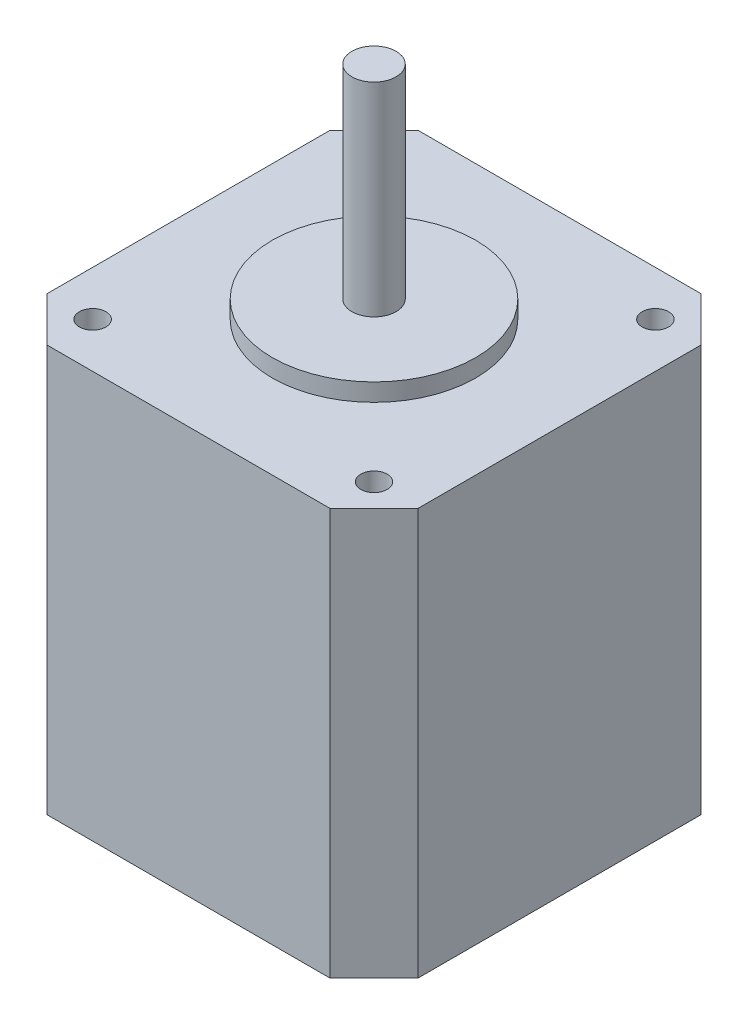
SolidWorks part; units mm, degrees
ref_plane "Front Plane" through (0, 0, 0) normal (0, 0, 1) x (1, 0, 0)
ref_plane "Top Plane" through (0, 0, 0) normal (0, 1, 0) x (1, 0, 0)
ref_plane "Right Plane" through (0, 0, 0) normal (1, 0, 0) x (0, 0, -1)
sketch "Sketch1" plane through (0, 0, 0) normal (0, 1, 0) x (1, 0, 0)
  line L1 (-21, -21) -> (21, -21)
  line L2 (-21, -21) -> (-21, 21)
  line L3 (-21, 21) -> (21, 21)
  line L4 (21, -21) -> (21, 21)
  line L5 (-21, -21) -> (21, 21) construction
  line L6 (-21, 21) -> (21, -21) construction
  point P0 (0, 0)
  dimension "D1" = 42
  dimension "D2" = 42
extrude "Boss-Extrude1" add sketch "Sketch1" along normal blind 46
chamfer "Chamfer1" distance 5 angle 45 4 edges at (-21, 23, -21) (21, 23, -21) (21, 23, 21) (-21, 23, 21)
sketch "Sketch2" plane through (0, 46, 0) normal (0, 1, 0) x (1, 0, 0)
  circle A0 centre (0, 0) radius 11.5
  dimension "D1" = 23
extrude "Boss-Extrude2" add sketch "Sketch2" along normal blind 2
sketch "Sketch3" plane through (0, 46, 0) normal (0, 1, 0) x (1, 0, 0)
  circle A0 centre (0, 0) radius 2.5
  dimension "D1" = 5
extrude "Boss-Extrude3" add sketch "Sketch3" along normal blind 25
sketch "Sketch4" plane through (0, 46, 0) normal (0, 1, 0) x (1, 0, 0)
  line L0 (-15.9099, -15.9099) -> (-15.9099, 15.9099) construction
  line L1 (-15.9099, 15.9099) -> (15.9099, 15.9099) construction
  circle A0 centre (0, 0) radius 22.5 construction
  circle A1 centre (-15.9099, 15.9099) radius 1.5
  circle A2 centre (15.9099, 15.9099) radius 1.5
  circle A3 centre (15.9099, -15.9099) radius 1.5
  circle A4 centre (-15.9099, -15.9099) radius 1.5
  dimension "D1" = 45
  dimension "D2" = 3
extrude "Cut-Extrude1" cut sketch "Sketch4" against normal blind 5
